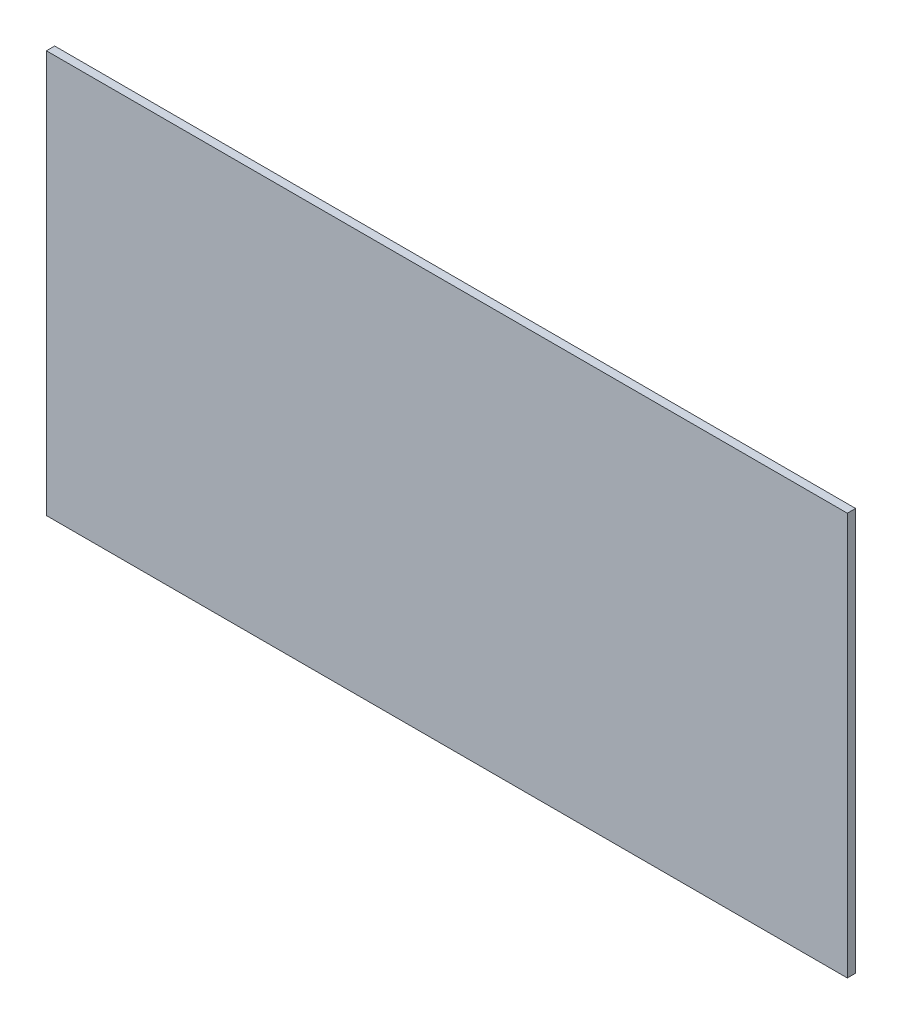
SolidWorks part; units mm, degrees
material "Akryl (středně-vysoký dopad)"
ref_plane "Přední rovina" through (0, 0, 0) normal (0, 0, 1) x (1, 0, 0)
ref_plane "Horní rovina" through (0, 0, 0) normal (0, 1, 0) x (1, 0, 0)
ref_plane "Pravá rovina" through (0, 0, 0) normal (1, 0, 0) x (0, 0, -1)
sketch "Skica1" plane through (0, 0, 0) normal (0, 0, 1) x (1, 0, 0)
  line L1 (194, -97.5) -> (-194, -97.5)
  line L2 (194, -97.5) -> (194, 97.5)
  line L3 (194, 97.5) -> (-194, 97.5)
  line L4 (-194, -97.5) -> (-194, 97.5)
  line L5 (194, -97.5) -> (-194, 97.5) construction
  line L6 (194, 97.5) -> (-194, -97.5) construction
  point P0 (0, 0)
  dimension "D1" = 388
  dimension "D2" = 195
extrude "Přidat vysunutím1" add sketch "Skica1" along normal blind 4
